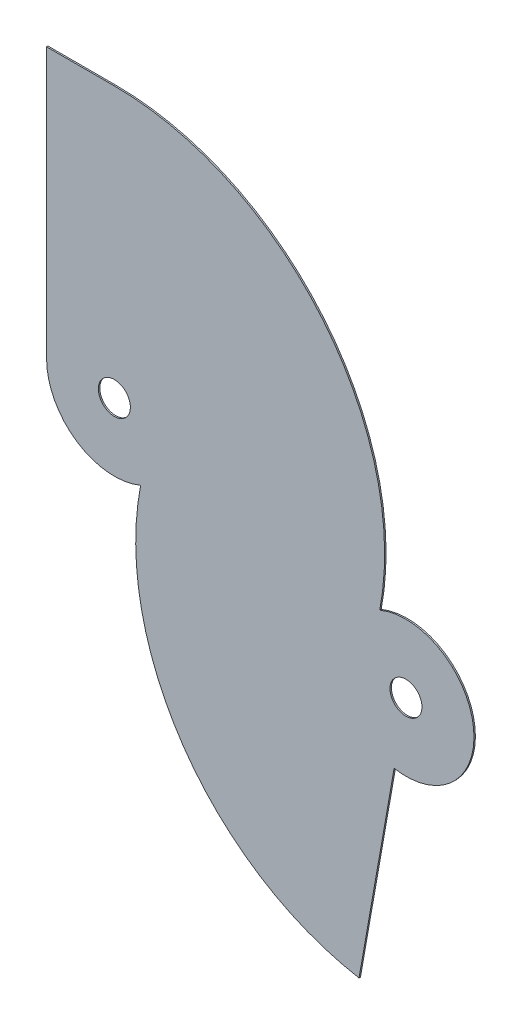
SolidWorks part; units mm, degrees
ref_plane "Front Plane" through (0, 0, 0) normal (0, 0, 1) x (1, 0, 0)
ref_plane "Top Plane" through (0, 0, 0) normal (0, 1, 0) x (1, 0, 0)
ref_plane "Right Plane" through (0, 0, 0) normal (1, 0, 0) x (0, 0, -1)
sketch "Sketch1" plane through (0, 0, 0) normal (0, 0, 1) x (1, 0, 0)
  line L1 (0, 0) -> (431.8, 0)
  line L2 (0, 0) -> (0, 609.6)
  line L3 (0, 609.6) -> (431.8, 609.6)
  line L4 (431.8, 0) -> (431.8, 609.6)
  dimension "D1" = 609.6
  dimension "D2" = 431.8
extrude "Boss-Extrude1" add sketch "Sketch1" along normal blind 1.27
sketch "Sketch2" plane through (0, 0, 0) normal (0, 0, -1) x (-1, 0, 0)
  line L0 (0, 609.6) -> (0, 0) construction
  line L1 (0, 0) -> (-431.8, 0) construction
  line L2 (0, 0) -> (-431.8, 0) construction
  line L3 (0, 609.6) -> (0, 0) construction
  circle A0 centre (-82.55, 355.6) radius 14.2875
  circle A1 centre (-342.9, 254) radius 14.2875
  dimension "D1" = 82.55
  dimension "D3" = 28.575
  dimension "D4" = 28.575
  dimension "D2" = 355.6
  dimension "D5" = 254
  dimension "D6" = 342.9
extrude "Cut-Extrude1" cut sketch "Sketch2" against normal blind 1.27
sketch "Sketch3" plane through (0, 0, 0) normal (0, 0, -1) x (-1, 0, 0)
  line L2 (-332.3523, 194.181) -> (-300.9987, 16.3659)
  line L3 (-22.0333, 355.6) -> (-22.0333, 596.8999)
  line L4 (-22.0333, 596.8999) -> (-82.3089, 596.8999)
  arc A1 (-105.9876, 299.8062) -> (-300.9987, 16.3659) centre (-342.9, 254) cw
  arc A2 (-319.5136, 310.0593) -> (-332.3523, 194.181) centre (-342.9, 254) ccw
  arc A3 (-319.5136, 310.0593) -> (-82.3089, 596.8999) centre (-82.55, 355.6) cw
  arc A4 (-105.9876, 299.8062) -> (-22.0333, 355.6) centre (-82.55, 355.6) ccw
  dimension "D1" = 60.7418
  dimension "D2" = 60.5167
  dimension "D3" = 241.3
  dimension "D4" = 241.3
  dimension "D5" = 279.4721
  dimension "D6" = 101.6
extrude "Cut-Extrude2" cut sketch "Sketch3" against normal blind 2.54 flip side to cut
